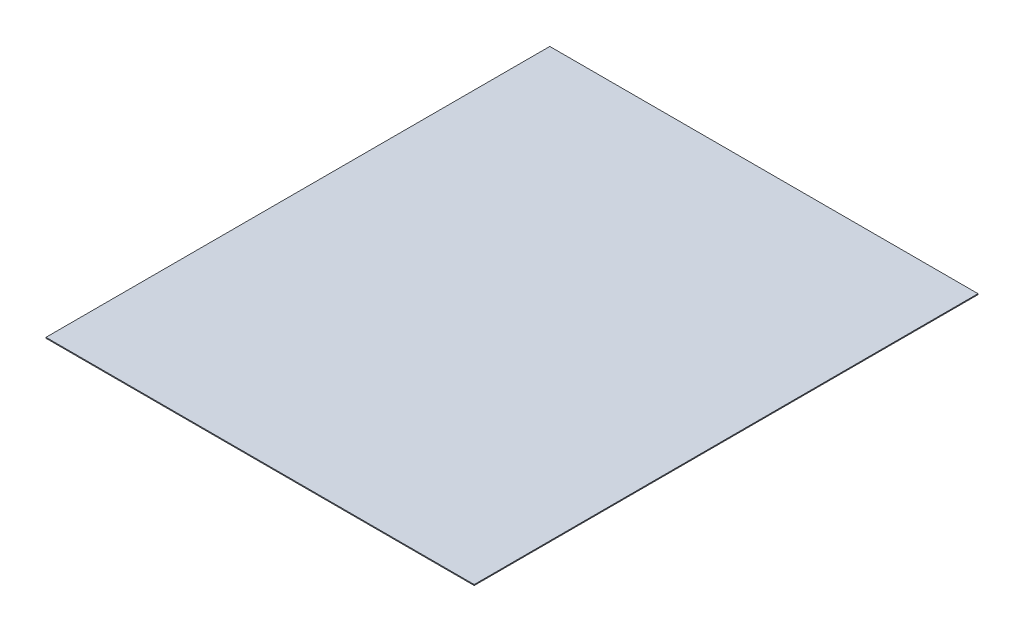
SolidWorks part; units mm, degrees
ref_plane "Front Plane" through (0, 0, 0) normal (0, 0, 1) x (1, 0, 0)
ref_plane "Top Plane" through (0, 0, 0) normal (0, 1, 0) x (1, 0, 0)
ref_plane "Right Plane" through (0, 0, 0) normal (1, 0, 0) x (0, 0, -1)
other "Configuration Table"
sketch "Sketch1" plane through (0, 0, 0) normal (0, 0, 1) x (1, 0, 0)
  line L1 (1.5, 1968.5) -> (698.5, 1968.5)
  line L2 (1.5, 1968.5) -> (1.5, 1970)
  line L3 (1.5, 1970) -> (698.5, 1970)
  line L4 (698.5, 1968.5) -> (698.5, 1970)
extrude "TOPPING_dis_ust_1" add sketch "Sketch1" against normal blind 820 separate body
